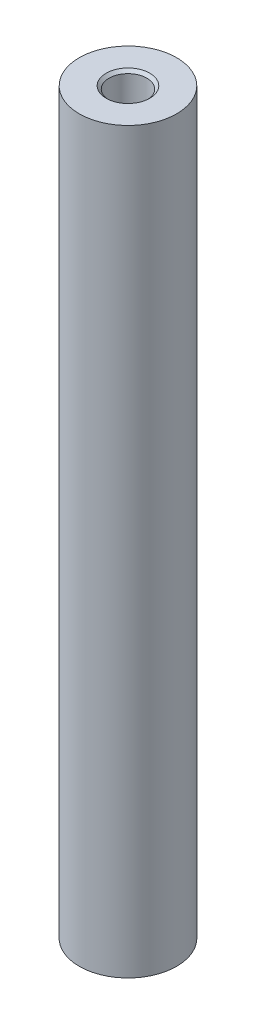
SolidWorks part; units mm, degrees
ref_plane "Front Plane" through (0, 0, 0) normal (0, 0, 1) x (1, 0, 0)
ref_plane "Top Plane" through (0, 0, 0) normal (0, 1, 0) x (1, 0, 0)
ref_plane "Right Plane" through (0, 0, 0) normal (1, 0, 0) x (0, 0, -1)
sketch "Sketch1" plane through (0, 0, 0) normal (0, 1, 0) x (1, 0, 0)
  circle A0 centre (0, 0) radius 5.07
  dimension "D1" = 10.14
extrude "Boss-Extrude1" add sketch "Sketch1" along normal blind 76.9
sketch "Sketch2" plane through (0, 76.9, 0) normal (0, 1, 0) x (1, 0, 0)
  circle A0 centre (0, 0) radius 1.97
  dimension "D1" = 3.94
extrude "Cut-Extrude1" cut sketch "Sketch2" against normal blind 15.2
chamfer "Chamfer2" distance 0.3 1 edges at (0, 76.9, 1.97)
sketch "Sketch3" plane through (0, 0, 0) normal (0, -1, 0) x (-1, 0, 0)
  circle A0 centre (0, 0) radius 1.97
  dimension "D1" = 3.94
extrude "Cut-Extrude2" cut sketch "Sketch3" against normal blind 15.2
chamfer "Chamfer3" distance 0.3 1 edges at (0, 0, -1.97)
